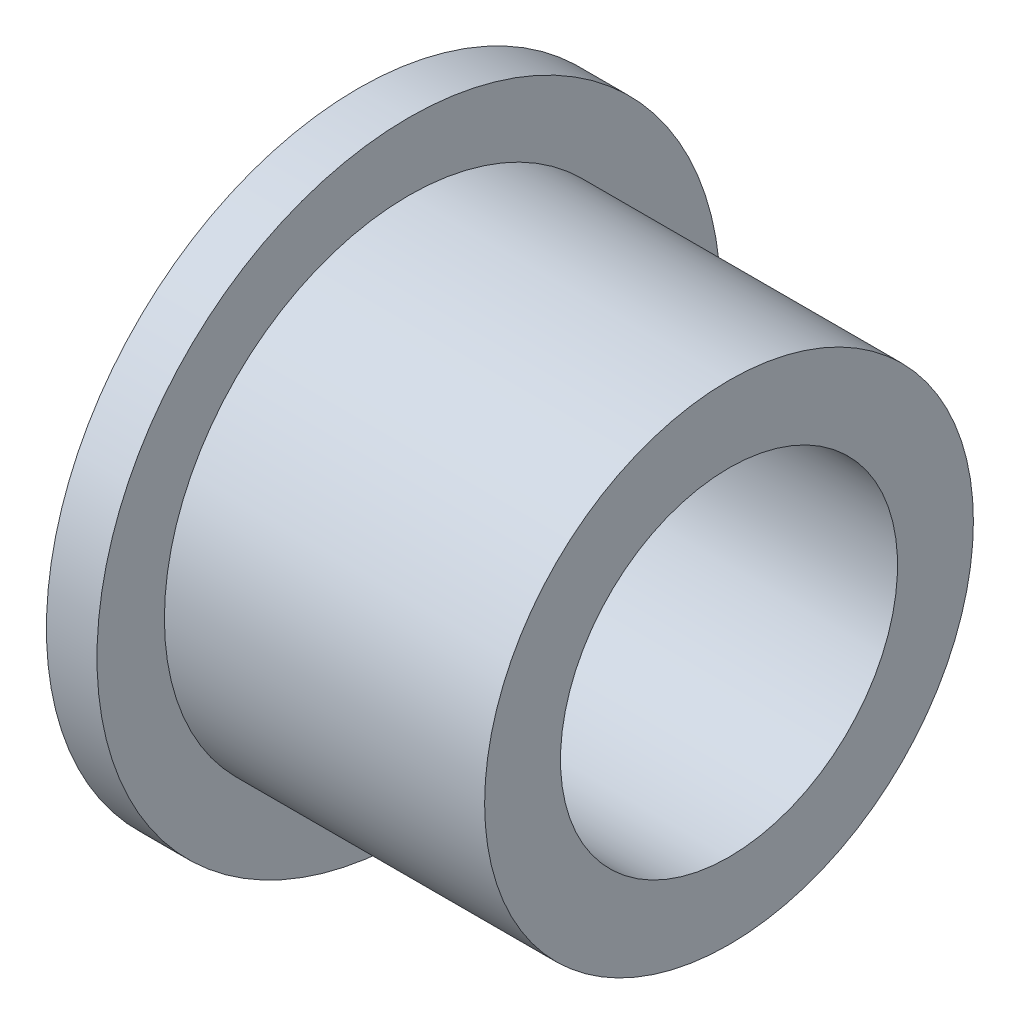
SolidWorks part; units mm, degrees
ref_plane "face" through (0, 0, 0) normal (0, 0, 1) x (1, 0, 0)
ref_plane "dessus" through (0, 0, 0) normal (0, 1, 0) x (1, 0, 0)
ref_plane "droite" through (0, 0, 0) normal (1, 0, 0) x (0, 0, -1)
sketch "Esquisse2" plane through (0, 0, 0) normal (0, 0, 1) x (1, 0, 0)
  line L0 (0, 10) -> (0, 18.5)
  line L1 (0, 18.5) -> (3, 18.5)
  line L2 (3, 18.5) -> (3, 14.5)
  line L3 (3, 14.5) -> (22, 14.5)
  line L4 (22, 14.5) -> (22, 10)
  line L5 (0, 0) -> (60, 0) construction
  line L7 (22, 10) -> (0, 10)
  dimension "D1" = 18.5
  dimension "D2" = 22
  dimension "D3" = 19
  dimension "D4" = 4
  dimension "D5" = 4.5
  dimension "D7" = 10
revolve "Base-Révolution" add sketch "Esquisse2" angle 360 about L5
